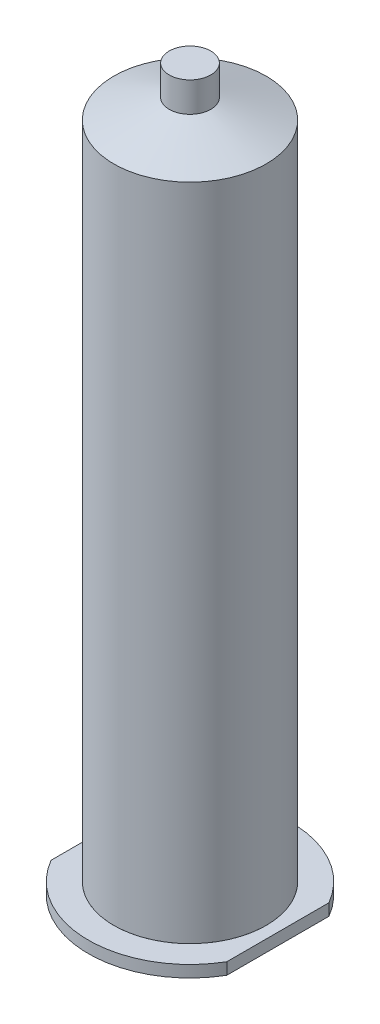
SolidWorks part; units mm, degrees
ref_plane "Front Plane" through (0, 0, 0) normal (0, 0, 1) x (1, 0, 0)
ref_plane "Top Plane" through (0, 0, 0) normal (0, 1, 0) x (1, 0, 0)
ref_plane "Right Plane" through (0, 0, 0) normal (1, 0, 0) x (0, 0, -1)
sketch "Sketch1" plane through (0, 0, 0) normal (0, 0, 1) x (1, 0, 0)
  line L0 (4.775, 156) -> (17.5, 151.5)
  line L1 (0, 0) -> (17.5, 0)
  line L2 (0, 0) -> (0, 151.5)
  line L3 (0, 151.5) -> (17.5, 151.5)
  line L4 (17.5, 0) -> (17.5, 151.5)
  line L5 (4.775, 151.5) -> (0, 151.5)
  line L6 (4.775, 151.5) -> (4.775, 162.85)
  line L7 (4.775, 162.85) -> (0, 162.85)
  line L8 (0, 151.5) -> (0, 162.85)
  dimension "D1" = 151.5
  dimension "D2" = 17.5
  dimension "D3" = 4.775
  dimension "D4" = 11.35
  dimension "D5" = 4.5
revolve "Revolve1" add sketch "Sketch1" angle 360 about L2
shell "Shell1" thickness 4
sketch "Sketch2" plane through (0, 0, 0) normal (0, -1, 0) x (1, 0, 0)
  line L1 (-20.185, -29.7439) -> (20.185, -29.7439)
  line L2 (-20.185, -29.7439) -> (-20.185, 29.7439)
  line L3 (-20.185, 29.7439) -> (20.185, 29.7439)
  line L4 (20.185, -29.7439) -> (20.185, 29.7439)
  line L5 (-20.185, -29.7439) -> (20.185, 29.7439) construction
  line L6 (-20.185, 29.7439) -> (20.185, -29.7439) construction
  circle A0 centre (0, 0) radius 23.35
  circle M5 centre (0, 0) radius 17.5
  dimension "D1" = 46.7
  dimension "D2" = 40.37
extrude "Boss-Extrude1" add sketch "Sketch2" along normal blind 2.7 separate body contours L4 A0 L2 M5
